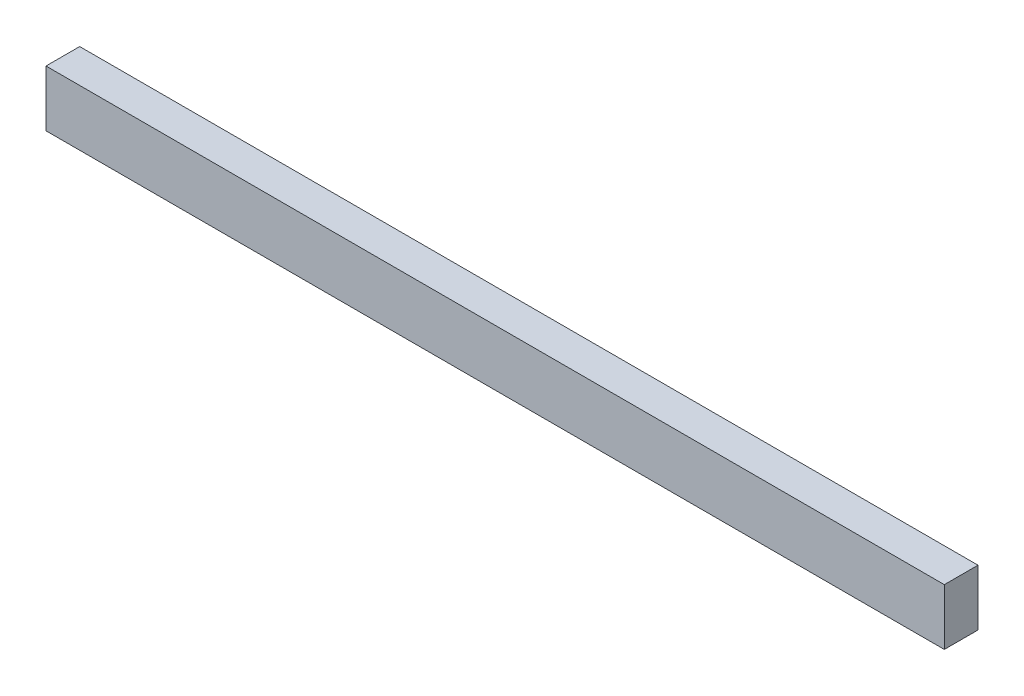
SolidWorks part; units mm, degrees
material "ABS"
ref_plane "Front Plane" through (0, 0, 0) normal (0, 0, 1) x (1, 0, 0)
ref_plane "Top Plane" through (0, 0, 0) normal (0, 1, 0) x (1, 0, 0)
ref_plane "Right Plane" through (0, 0, 0) normal (1, 0, 0) x (0, 0, -1)
sketch "Sketch1" plane through (0, 0, 0) normal (0, 0, 1) x (1, 0, 0)
  line L0 (0, 2.5) -> (0, 0) construction
  line L1 (-40, 2.5) -> (40, 2.5)
  line L2 (-40, 2.5) -> (-40, -2.5)
  line L3 (-40, -2.5) -> (40, -2.5)
  line L4 (40, 2.5) -> (40, -2.5)
  line L5 (0, 0) -> (0, -2.5) construction
  dimension "D1" = 80
  dimension "D2" = 5
extrude "Boss-Extrude1" add sketch "Sketch1" along normal blind 3
